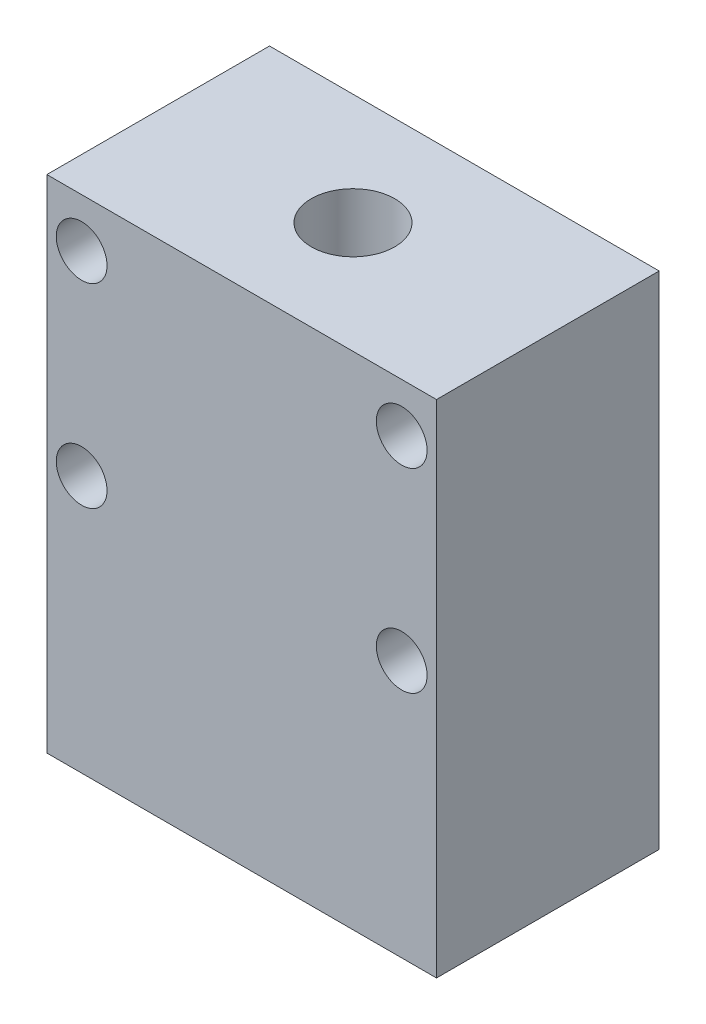
SolidWorks part; units mm, degrees
material "Rubber"
ref_plane "Front Plane" through (0, 0, 0) normal (0, 0, 1) x (1, 0, 0)
ref_plane "Top Plane" through (0, 0, 0) normal (0, 1, 0) x (1, 0, 0)
ref_plane "Right Plane" through (0, 0, 0) normal (1, 0, 0) x (0, 0, -1)
sketch "Sketch1" plane through (0, 0, 0) normal (0, 1, 0) x (1, 0, 0)
  line L1 (-22.225, 12.7) -> (22.225, 12.7)
  line L2 (-22.225, 12.7) -> (-22.225, -12.7)
  line L3 (-22.225, -12.7) -> (22.225, -12.7)
  line L4 (22.225, 12.7) -> (22.225, -12.7)
  line L5 (-22.225, 12.7) -> (22.225, -12.7) construction
  line L6 (-22.225, -12.7) -> (22.225, 12.7) construction
  point P0 (0, 0)
  dimension "D1" = 44.45
  dimension "D2" = 25.4
extrude "Boss-Extrude1" add sketch "Sketch1" along normal blind 57.15
sketch "Sketch2" plane through (0, 57.15, 0) normal (0, 1, 0) x (1, 0, 0)
  line L0 (-22.225, -12.7) -> (22.225, -12.7) construction
  line L1 (22.225, -12.7) -> (22.225, 12.7) construction
  circle A0 centre (0, 0) radius 4.7625
  dimension "D1" = 9.525
  dimension "D3" = 22.225
  dimension "D2" = 12.7
extrude "Cut-Extrude1" cut sketch "Sketch2" against normal up to next
hole_wizard "#12 Clearance Hole1" positions "Sketch4" profile "Sketch5" hole size "#12" standard "ANSI Inch" end condition up to next
sketch "Sketch4" plane through (0, 0, 12.7) normal (0, 0, 1) x (1, 0, 0)
  line L1 (-18.2563, 51.5874) -> (18.2562, 51.5874) construction
  line L2 (-18.2563, 51.5874) -> (-18.2562, 29.3624) construction
  line L3 (-18.2562, 29.3624) -> (18.2562, 29.3624) construction
  line L4 (18.2562, 51.5874) -> (18.2562, 29.3624) construction
  line L5 (0, 51.5874) -> (0, 57.15) construction
  line L6 (-22.225, 57.15) -> (22.225, 57.15) construction
  point P0 (-18.2563, 51.5874)
  point P1 (18.2562, 29.3624)
  point P206 (-18.2562, 29.3624)
  point P207 (18.2562, 51.5874)
  dimension "D1" = 22.225
  dimension "D2" = 36.5125
  dimension "D3" = 5.5626
sketch "Sketch5" plane through (-18.2563, 51.5874, 12.7) normal (1, 0, 0) x (0, -1, 0)
  line L0 (0, 0) -> (0, 25.4)
  line L1 (0, 25.4) -> (2.8956, 25.4)
  line L2 (2.8956, 25.4) -> (2.8956, 0)
  line L5 (2.8956, 0) -> (0, 0)
  line L11 (0, -6.35) -> (0, 107.95) construction
  dimension "Thru Hole Dia." = 5.7912
  dimension "Thru Hole Depth" = 25.4
